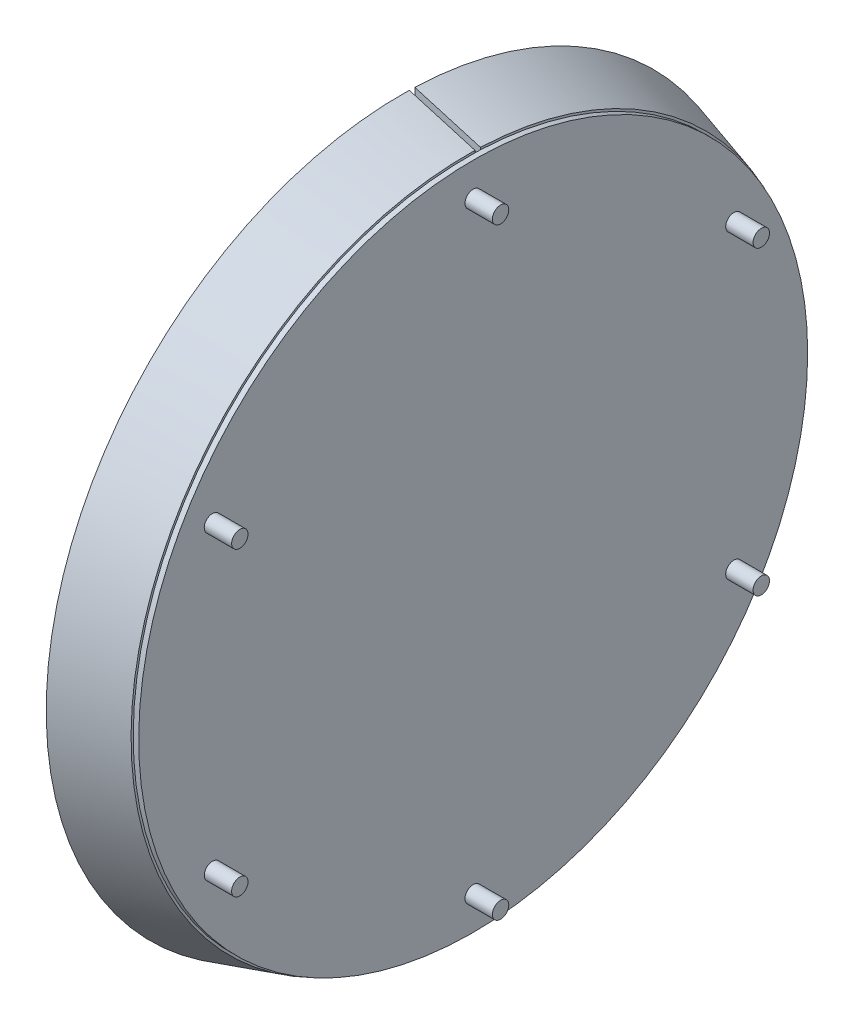
SolidWorks part; units mm, degrees
material "AISI 316 Stainless Steel Sheet (SS)"
ref_plane "Front Plane" through (0, 0, 0) normal (0, 0, 1) x (1, 0, 0)
ref_plane "Top Plane" through (0, 0, 0) normal (0, 1, 0) x (1, 0, 0)
ref_plane "Right Plane" through (0, 0, 0) normal (1, 0, 0) x (0, 0, -1)
sketch "Sketch2" plane through (0, 0, 0) normal (0, 0, 1) x (1, 0, 0)
  line L0 (0, 0) -> (58922.4238, 0) construction
  line L1 (1.5723, 73.5) -> (58923.9961, 73.5) construction
  line L2 (0, 65) -> (0, 63.5)
  line L3 (0, 63.5) -> (12, 60)
  line L4 (12, 60) -> (12, 61.5)
  line L5 (12, 61.5) -> (0, 65)
  dimension "D1" = 73.5
  dimension "D2" = 8.5
  dimension "D3" = 1.5
  dimension "D4" = 1.5
  dimension "D5" = 12
  dimension "D6" = 12
  dimension "D7" = 63.5
revolve "Revolve1" add sketch "Sketch2" angle 360 about L0
sketch "Sketch3" plane through (12, 0, 0) normal (1, 0, 0) x (0, 0, -1)
  line L1 (1.328, 69.3356) -> (2.328, 69.3356)
  line L2 (1.328, 69.3356) -> (1.328, 60.3356)
  line L3 (1.328, 60.3356) -> (2.328, 60.3356)
  line L4 (2.328, 69.3356) -> (2.328, 60.3356)
  dimension "D1" = 1
  dimension "D2" = 9
extrude "Cut-Extrude1" cut sketch "Sketch3" against normal up to surface (12 mm away) up to face at (0, 0, 63.5)
sketch "Sketch7" plane through (12, 0, 0) normal (1, 0, 0) x (0, 0, -1)
  circle A0 centre (0, 0) radius 61.1027
extrude "Boss-Extrude1" add sketch "Sketch7" along normal blind 1
sketch "Sketch8" plane through (13, 0, 0) normal (1, 0, 0) x (0, 0, -1)
  circle A0 centre (0, 55) radius 1.5
  dimension "D1" = 55
extrude "Boss-Extrude2" add sketch "Sketch8" along normal blind 5
sketch "Sketch9" plane through (0, 0, 0) normal (0, 0, 1) x (1, 0, 0)
  line L0 (0, 0) -> (50000, 0) construction
pattern_circular "CirPattern1" count 6 over 360 about axis through (0, 0, 0) along (1, 0, 0) of "Boss-Extrude2"
sketch "Sketch10" plane through (18, 0, 0) normal (1, 0, 0) x (0, 0, -1)
  circle A0 centre (0, 0) radius 50.471
  circle A1 centre (0, 0) radius 60.5793
